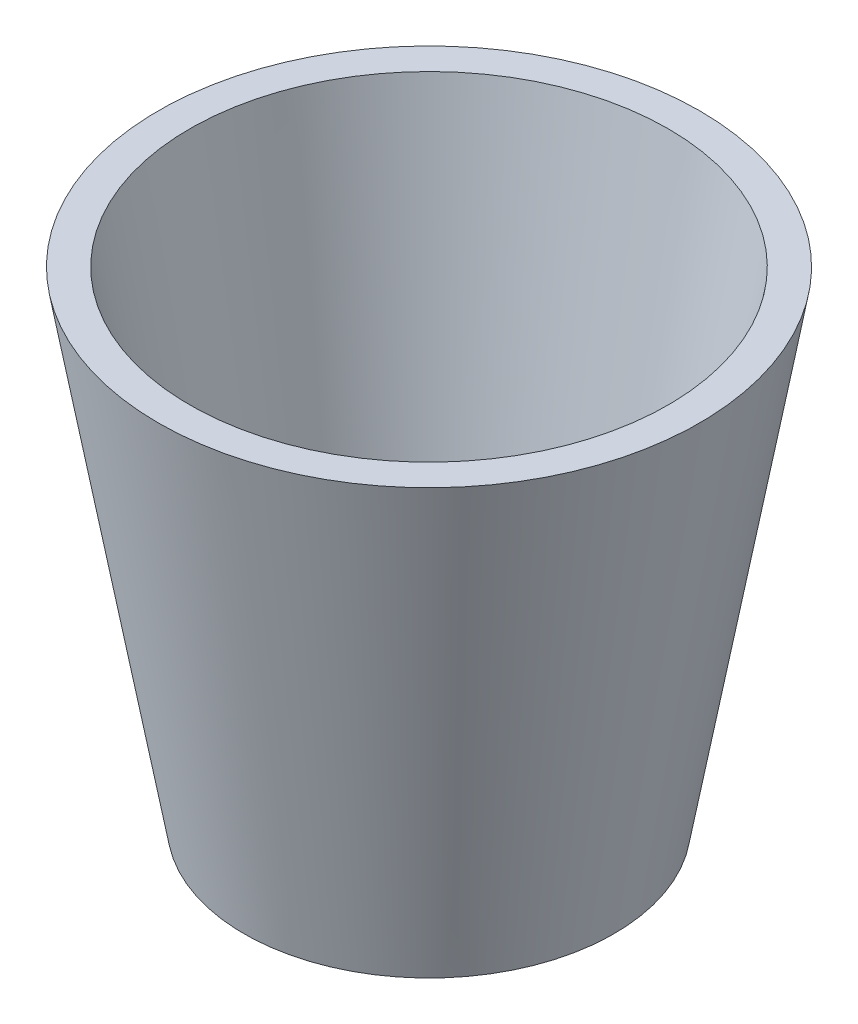
SolidWorks part; units mm, degrees
ref_plane "Front Plane" through (0, 0, 0) normal (0, 0, 1) x (1, 0, 0)
ref_plane "Top Plane" through (0, 0, 0) normal (0, 1, 0) x (1, 0, 0)
ref_plane "Right Plane" through (0, 0, 0) normal (1, 0, 0) x (0, 0, -1)
sketch "Sketch1" plane through (0, 0, 0) normal (0, 0, 1) x (1, 0, 0)
  line L0 (0, 0) -> (12, 0)
  line L2 (12, 0) -> (17.5487, 31.4683)
  line L8 (0, 2) -> (10.3218, 2)
  line L9 (10.3218, 2) -> (15.5179, 31.4683)
  line L10 (0, 0) -> (0, 2)
  line L12 (15.5179, 31.4683) -> (17.5487, 31.4683)
  line L14 (10.3218, 2) -> (17.489, 42.6473) construction
  line L15 (12, 0) -> (19.4586, 42.3) construction
  dimension "D1" = 12
  dimension "D2" = 2
  dimension "D4" = 80
revolve "Revolve1" add sketch "Sketch1" angle 360 about L10
